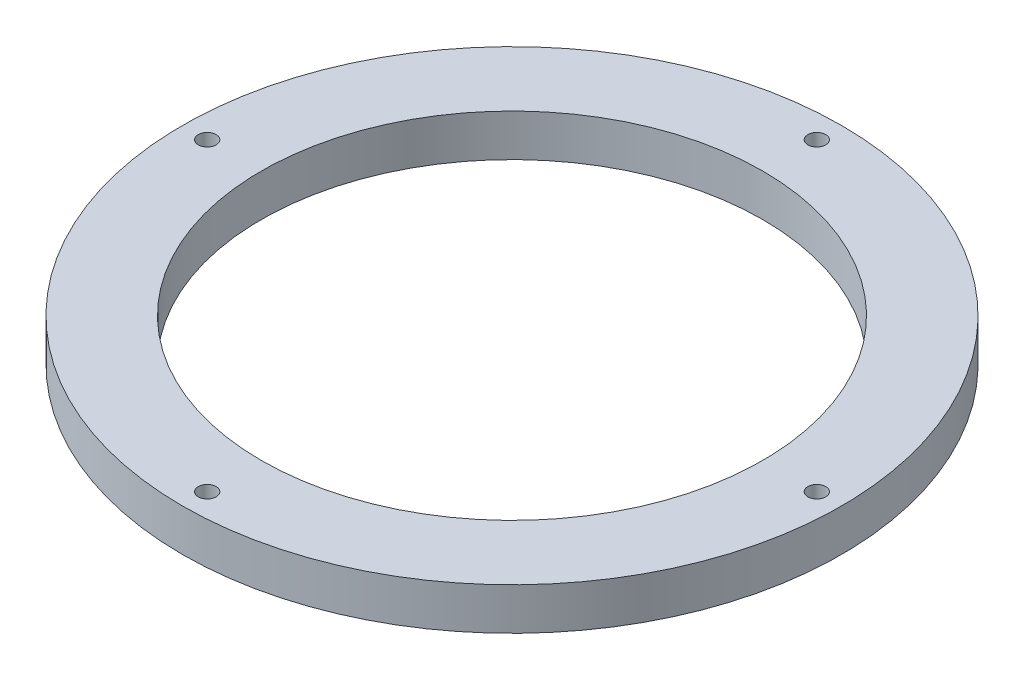
SolidWorks part; units mm, degrees
ref_plane "Front Plane" through (0, 0, 0) normal (0, 0, 1) x (1, 0, 0)
ref_plane "Top Plane" through (0, 0, 0) normal (0, 1, 0) x (1, 0, 0)
ref_plane "Right Plane" through (0, 0, 0) normal (1, 0, 0) x (0, 0, -1)
sketch "Sketch1" plane through (0, 0, 0) normal (0, 0, 1) x (1, 0, 0)
  line L0 (47.6885, 0) -> (47.6885, 8)
  line L1 (47.6885, 8) -> (62.6885, 8)
  line L2 (62.6885, 8) -> (62.6885, 0)
  line L3 (62.6885, 0) -> (47.6885, 0)
  line L4 (0, 0) -> (0, 31.9043) construction
  line L5 (0, 0) -> (15.8965, 0) construction
  line L6 (62.6885, 8) -> (62.6885, 33.4) construction
  dimension "D2" = 8
  dimension "D3" = 15
revolve "Revolve1" add sketch "Sketch1" angle 360 about L4
sketch "Sketch2" plane through (0, 0, 0) normal (0, -1, 0) x (1, 0, 0)
  circle A0 centre (0, -57.9825) radius 2.2 construction
  circle A1 centre (57.9825, 0) radius 2.2 construction
  circle A2 centre (-57.9825, 0) radius 2.2 construction
  circle A3 centre (0, 57.9825) radius 2.2 construction
  circle A8 centre (0, -57.9825) radius 2.2 construction
  circle A9 centre (57.9825, 0) radius 2.2 construction
  circle A10 centre (-57.9825, 0) radius 2.2 construction
  circle A11 centre (0, 57.9825) radius 2.2 construction
  point P0 (0, -57.9825)
  point P2 (57.9825, 0)
  point P4 (-57.9825, 0)
  point P6 (0, 57.9825)
hole_wizard "CBORE for M3 Hex Head Machine Screw1" positions "Sketch2" profile "Sketch3" counterbore size "M3" standard "ANSI Metric" end condition through all
sketch "Sketch3" plane through (0, 0, -57.9825) normal (1, 0, 0) x (0, 0, -1)
  line L0 (0, 0) -> (0, 8)
  line L1 (0, 8) -> (1.7, 8)
  line L3 (1.7, 8) -> (1.7, 2.3)
  line L4 (4.2, 2.3) -> (1.7, 2.3)
  line L5 (4.2, 2.3) -> (4.2, 0.025)
  line L6 (4.2, 0.025) -> (4.225, 0)
  line L7 (4.225, 0) -> (0, 0)
  line L8 (-4.2, 0.025) -> (-4.225, 0) construction
  line L11 (0, -6.35) -> (0, 107.95) construction
  dimension "Thru Hole Dia." = 3.4
  dimension "Thru Hole Depth" = 8
  dimension "C'Bore Dia." = 8.4
  dimension "C'Bore Depth" = 2.3
  dimension "Near C'Sink Dia." = 8.45
  dimension "Near C'Sink Angle" = 90
